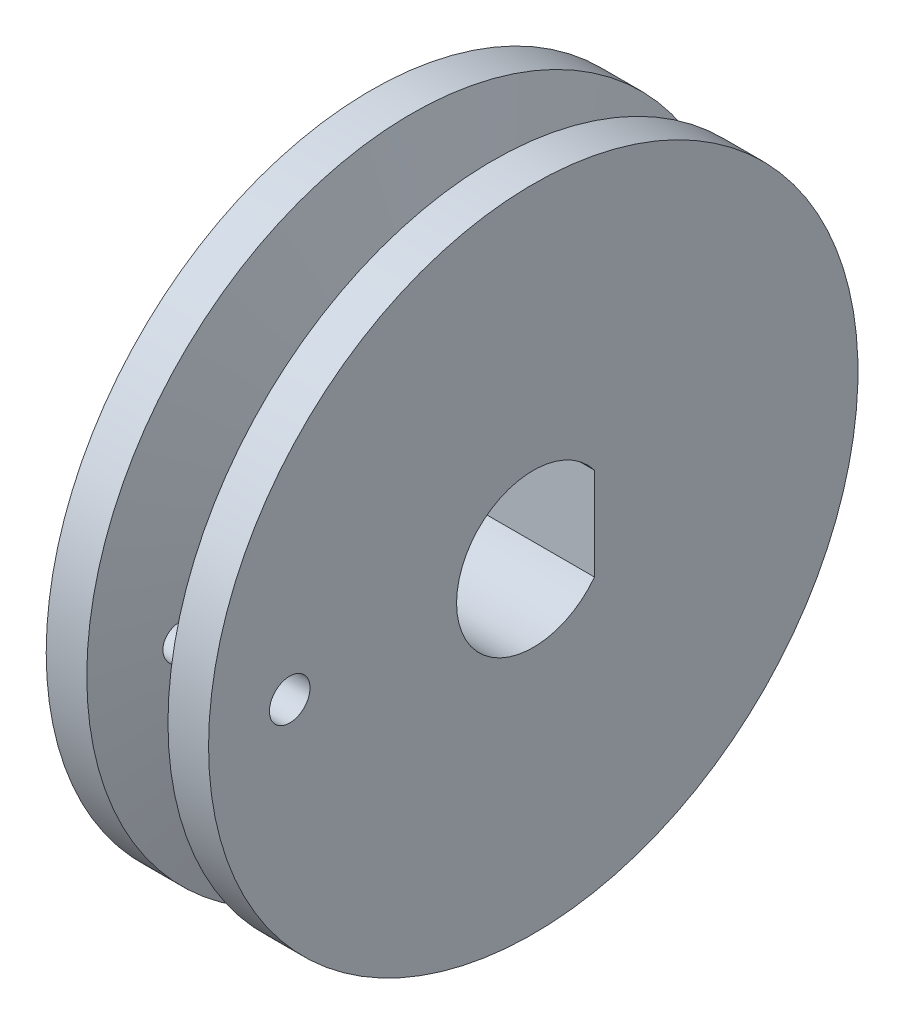
SolidWorks part; units mm, degrees
ref_plane "Front Plane" through (0, 0, 0) normal (0, 0, 1) x (1, 0, 0)
ref_plane "Top Plane" through (0, 0, 0) normal (0, 1, 0) x (1, 0, 0)
ref_plane "Right Plane" through (0, 0, 0) normal (1, 0, 0) x (0, 0, -1)
sketch "Sketch2" plane through (0, 0, 0) normal (0, 0, 1) x (1, 0, 0)
  line L0 (0, 0) -> (28.9983, 0) construction
  line L1 (0, 0) -> (0, 12.7)
  line L2 (0, 12.7) -> (1.5875, 12.7)
  line L3 (1.5875, 12.7) -> (3.175, 6.35)
  line L4 (3.175, 6.35) -> (4.7625, 12.7)
  line L5 (4.7625, 12.7) -> (6.35, 12.7)
  line L6 (6.35, 12.7) -> (6.35, 0)
  line L7 (0, 6.35) -> (6.35, 6.35) construction
  line L8 (0, 0) -> (6.35, 0)
  dimension "D1" = 1.5875
  dimension "D2" = 12.7
  dimension "D3" = 6.35
  dimension "D4" = 6.35
revolve "Revolve1" add sketch "Sketch2" angle 360 about L0
sketch "Sketch3" plane through (6.35, 0, 0) normal (1, 0, 0) x (0, 0, -1)
  line L0 (2.3929, -1.8094) -> (2.3929, 1.8094)
  line L1 (3, 2.5745) -> (3, -1.9178) construction
  arc A0 (2.3929, 1.8094) -> (2.3929, -1.8094) centre (0, 0) ccw
  arc A1 (2.3929, 1.8094) -> (2.3929, -1.8094) centre (0, 0) cw construction
  dimension "D2" = 3
  dimension "D1" = 0.6071
extrude "Cut-Extrude1" cut sketch "Sketch3" against normal through all both and the other way through all
sketch "Sketch4" plane through (6.35, 0, 0) normal (1, 0, 0) x (0, 0, -1)
  line L0 (-6.35, 0) -> (-12.7, 0) construction
  circle A0 centre (0, 0) radius 6.35 construction
  circle A1 centre (0, 0) radius 6.35 construction
  circle A2 centre (-9.525, 0) radius 0.7937
  circle A3 centre (0, 0) radius 12.7 construction
  point P10 (0, 0)
  dimension "D1" = 1.5875
extrude "Cut-Extrude2" cut sketch "Sketch4" against normal through all both and the other way through all
